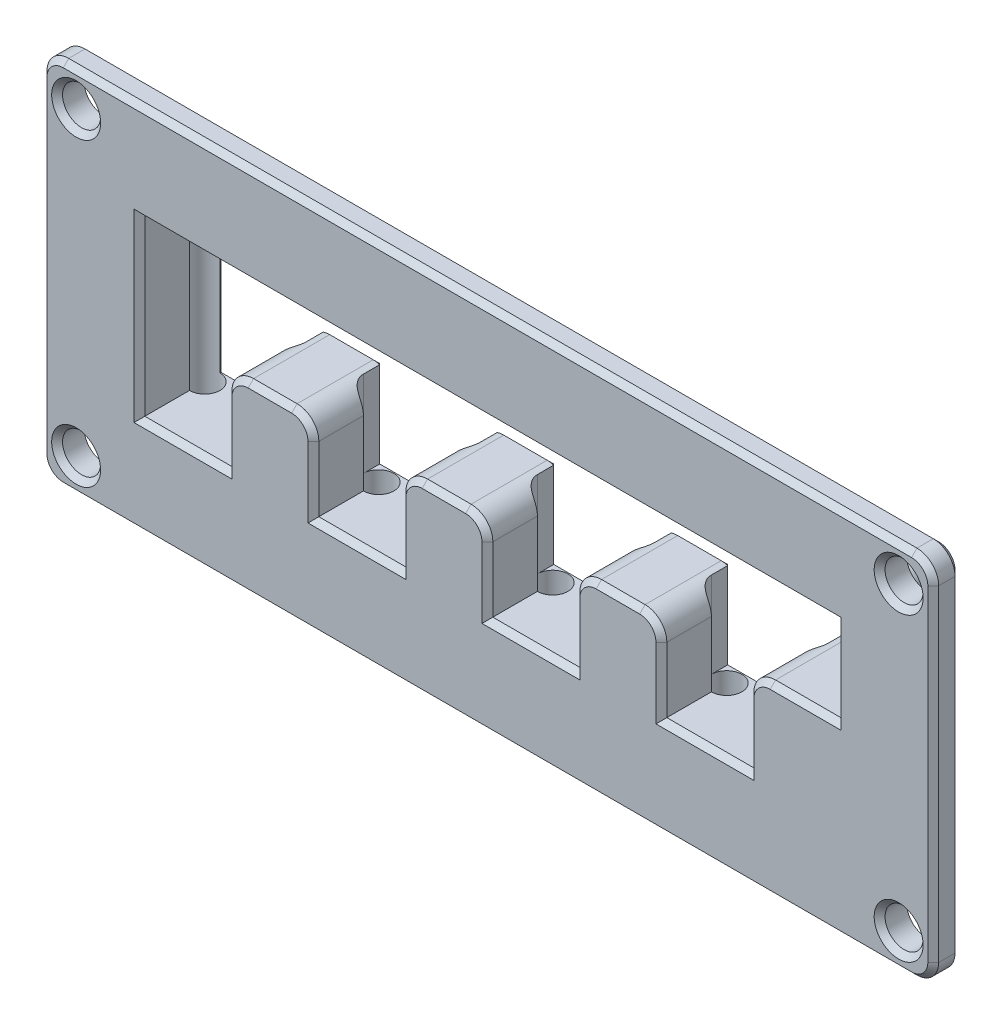
SolidWorks part; units mm, degrees
ref_plane "Front Plane" through (0, 0, 0) normal (0, 0, 1) x (1, 0, 0)
ref_plane "Top Plane" through (0, 0, 0) normal (0, 1, 0) x (1, 0, 0)
ref_plane "Right Plane" through (0, 0, 0) normal (1, 0, 0) x (0, 0, -1)
sketch "Sketch1" plane through (0, 0, 0) normal (0, 0, 1) x (1, 0, 0)
  line L0 (-35, 3) -> (35, 3)
  line L1 (-35, 3) -> (-35, -19)
  line L2 (35, 3) -> (35, -19)
  line L3 (-35, -19) -> (35, -19)
  line L4 (0, 0) -> (0, 3) construction
  line L5 (-32, -8) -> (-35, -8) construction
  line L6 (-32, 0) -> (-32, -16) construction
  line L7 (32, 0) -> (-32, 0) construction
  line L8 (-32, -16) -> (-24, -16) construction
  line L9 (-24, -16) -> (-24, -8) construction
  line L10 (-24, -8) -> (-16, -8) construction
  line L11 (-16, -8) -> (-16, -16) construction
  line L12 (-16, -16) -> (-8, -16) construction
  line L13 (-8, -16) -> (-8, -8) construction
  line L14 (-8, -8) -> (0, -8) construction
  line L15 (0, -8) -> (0, -16) construction
  line L16 (0, -16) -> (8, -16) construction
  line L17 (8, -16) -> (8, -8) construction
  line L18 (8, -8) -> (16, -8) construction
  line L19 (16, -8) -> (16, -16) construction
  line L20 (16, -16) -> (24, -16) construction
  line L21 (24, -16) -> (24, -8) construction
  line L22 (24, -8) -> (32, -8) construction
  line L23 (32, -8) -> (32, 0) construction
  line L24 (-32, 0) -> (-32, -16)
  line L25 (32, 0) -> (-32, 0)
  line L26 (-32, -16) -> (-24, -16)
  line L27 (-24, -16) -> (-24, -8)
  line L28 (-24, -8) -> (-16, -8)
  line L29 (-16, -8) -> (-16, -16)
  line L30 (-16, -16) -> (-8, -16)
  line L31 (-8, -16) -> (-8, -8)
  line L32 (-8, -8) -> (0, -8)
  line L33 (0, -8) -> (0, -16)
  line L34 (0, -16) -> (8, -16)
  line L35 (8, -16) -> (8, -8)
  line L36 (8, -8) -> (16, -8)
  line L37 (16, -8) -> (16, -16)
  line L38 (16, -16) -> (24, -16)
  line L39 (24, -16) -> (24, -8)
  line L40 (24, -8) -> (32, -8)
  line L41 (32, -8) -> (32, 0)
  dimension "D1" = 3
extrude "Boss-Extrude1" add sketch "Sketch1" against normal blind 8
sketch "Sketch2" plane through (0, 0, 0) normal (0, 0, 1) x (1, 0, 0)
  line L0 (0, 3) -> (0, 9) construction
  line L1 (-41, 9) -> (41, 9)
  line L2 (-41, 9) -> (-41, -25)
  line L3 (-41, -25) -> (41, -25)
  line L4 (41, 9) -> (41, -25)
  line L5 (-35, 3) -> (35, 3)
  line L6 (-35, 3) -> (-35, -19)
  line L7 (-35, -19) -> (35, -19)
  line L8 (35, 3) -> (35, -19)
  line L9 (-35, -8) -> (-41, -8) construction
  dimension "D1" = 6
extrude "Boss-Extrude2" add sketch "Sketch2" against normal blind 2.5
sketch "Sketch6" plane through (0, 0, -2.5) normal (0, 0, -1) x (-1, 0, 0)
  line L0 (35, -19) -> (37.818, -21.818) construction
  line L2 (-41, 9) -> (-37.818, 5.818) construction
  line L3 (-37.818, 5.818) -> (-35, 3) construction
  line L4 (37.818, -21.818) -> (-37.818, -21.818) construction
  line L5 (37.818, -21.818) -> (37.818, 5.818) construction
  line L6 (37.818, 5.818) -> (-37.818, 5.818) construction
  line L7 (-37.818, -21.818) -> (-37.818, 5.818) construction
  line L8 (38.7669, -18.2768) -> (35.2256, -19.2256) construction
  line L9 (35.2256, -19.2256) -> (34.2768, -22.7669) construction
  line L10 (34.2768, -22.7669) -> (36.8691, -25.3593) construction
  line L11 (36.8691, -25.3593) -> (40.4104, -24.4104) construction
  line L12 (40.4104, -24.4104) -> (41.3593, -20.8691) construction
  line L13 (41.3593, -20.8691) -> (38.7669, -18.2768) construction
  line L14 (37.818, -21.818) -> (41, -25) construction
  circle A0 centre (37.818, -21.818) radius 1.75
  circle A1 centre (37.818, -21.818) radius 3.175 construction
  circle A2 centre (37.818, -21.818) radius 3.6662 construction
  circle A3 centre (-37.818, 5.818) radius 1.75
  circle A4 centre (37.818, 5.818) radius 1.75
  circle A5 centre (-37.818, -21.818) radius 1.75
  dimension "D1" = 3.5
  dimension "D2" = 6.35
  dimension "D3" = 4.5
extrude "Cut-Extrude3" cut sketch "Sketch6" against normal up to next
fillet "Fillet1" radius 2 15 edges at (24, -8, -4) (16, -8, -4) (8, -8, -4) (0, -8, -4) (-8, -8, -4) (-16, -8, -4) (-24, -8, -4) (-41, -25, -1.25) (-41, 9, -1.25) (-35, -19, -5.25) (-35, 3, -5.25) (35, -19, -5.25) (35, 3, -5.25) (41, -25, -1.25) (41, 9, -1.25)
sketch "Sketch3" plane through (0, 0, 0) normal (0, 1, 0) x (1, 0, 0)
  circle A0 centre (-32, 6) radius 1.2 construction
  arc A1 (-32, 4.8) -> (-32, 7.2) centre (-32, 6) ccw construction
  circle A2 centre (-32, 6) radius 1.4
  dimension "D1" = 0.2
extrude "Cut-Extrude1" cut sketch "Sketch3" against normal through all both and the other way through all
pattern_linear "LPattern1" count 9 spacing 8 along (1, 0, 0) of "Cut-Extrude1"
sketch "Sketch4" plane through (0, 0, 0) normal (1, 0, 0) x (0, 0, -1)
  line L0 (4.875, -21.8042) -> (5.625, -23.1033) construction
  line L1 (8, -19) -> (2.5, -19) construction
  line L2 (8, -17) -> (8, -20)
  line L3 (7, -20) -> (8, -20) construction
  line L4 (6.5, -20.866) -> (4.875, -21.8042)
  line L5 (4.5, -22.4537) -> (4.5, -19) construction
  line L6 (5.625, -23.1033) -> (6.5, -22.5981)
  line L7 (2.5, -23) -> (2.5, 7) construction
  line L12 (2.5, -17) -> (8, -17)
  line L13 (2.5, 1) -> (2.5, -17)
  line L14 (2.5, -17) -> (8, -17)
  line L15 (8, -17) -> (8, 1)
  line L16 (8, 1) -> (2.5, 1)
  line L17 (8, 1) -> (2.5, 1)
  arc A0 (6, -19) -> (6.5, -20.866) centre (6, -20) cw
  arc A1 (8, -20) -> (6.5, -22.5981) centre (5, -20) cw
  arc A2 (4.875, -21.8042) -> (5.625, -23.1033) centre (5.25, -22.4537) ccw
  dimension "D4" = 1
  dimension "D1" = 1.5
  dimension "D2" = 1
  dimension "D3" = 2
  dimension "D5" = 30
  dimension "D6" = 0
extrude "Boss-Extrude3" [suppressed] add sketch "Sketch4" along normal up to surface and the other way up to surface
sketch "Sketch5" [suppressed] plane through (0, -19, 0) normal (0, -1, 0) x (1, 0, 0)
  line L0 (-35, -3) -> (35, -3) construction
  line L1 (-35, -3) -> (-30.6, -3)
  line L2 (-35, -3) -> (-35, -10)
  line L3 (-35, -10) -> (-30.6, -10)
  line L4 (-30.6, -3) -> (-30.6, -10)
  line L5 (-17.4, -3) -> (-6.6, -3)
  line L6 (-17.4, -3) -> (-17.4, -10)
  line L7 (-17.4, -10) -> (-6.6, -10)
  line L8 (-6.6, -3) -> (-6.6, -10)
  line L9 (35, -10) -> (-35, -10) construction
  line L10 (6.6, -3) -> (17.4, -3)
  line L11 (6.6, -3) -> (6.6, -10)
  line L12 (6.6, -10) -> (17.4, -10)
  line L13 (17.4, -3) -> (17.4, -10)
  line L14 (30.6, -3) -> (35, -3)
  line L15 (30.6, -3) -> (30.6, -10)
  line L16 (30.6, -10) -> (35, -10)
  line L17 (35, -3) -> (35, -10)
  circle A0 centre (-32, -5) radius 1.4 construction
  circle A1 centre (-16, -5) radius 1.4 construction
  circle A2 centre (-8, -5) radius 1.4 construction
  circle A3 centre (8, -5) radius 1.4 construction
  circle A4 centre (16, -5) radius 1.4 construction
  circle A5 centre (32, -5) radius 1.4 construction
  circle A6 centre (-24, -5) radius 2
  circle A7 centre (0, -5) radius 2
  circle A8 centre (24, -5) radius 2
  circle A9 centre (-24, -5) radius 1.4 construction
  circle A10 centre (0, -5) radius 1.4 construction
  circle A11 centre (24, -5) radius 1.4 construction
  dimension "D1" = 4
extrude "Cut-Extrude2" [suppressed] cut sketch "Sketch5" along normal through all
mirror "Mirror1" [suppressed]
ref_plane "Plane1" through (0, 0, -6) normal (0, 0, 1) x (1, 0, 0)
sketch "Sketch7" plane through (0, 0, -6) normal (0, 0, 1) x (1, 0, 0)
  line L0 (-24, -10) -> (-24, -16) construction
  line L1 (-24, -8.0921) -> (-22.6, -8.0921)
  line L2 (-24, -8.0921) -> (-24, -16)
  line L3 (-24, -16) -> (-22.6, -16)
  line L4 (-22.6, -8.0921) -> (-22.6, -16)
  line L5 (-20, -8) -> (-20, -19) construction
  line L6 (-24, -16) -> (-25.4, -16) construction
  line L9 (-33, -19) -> (33, -19) construction
  line L10 (-22, -8) -> (-18, -8) construction
extrude "Cut-Extrude5" cut sketch "Sketch7" against normal up to surface (2 mm away)
ref_plane "Plane2" through (-20, 0, 0) normal (1, 0, 0) x (0, 0, -1)
mirror "Mirror2" about plane through (-20, 0, 0) normal (1, 0, 0) of "Cut-Extrude5"
pattern_linear "LPattern3" count 4 spacing 16 along (1, 0, 0) of "Cut-Extrude5"
pattern_linear "LPattern4" count 3 spacing 16 along (1, 0, 0) of "Mirror2"
chamfer "Chamfer1" distance 0.5 angle 45 78 edges at (-40.4142, 8.4142, -2.5) (-40.4142, 8.4142, 0) (0, 9, 0) (40.4142, 8.4142, -2.5) (40.4142, 8.4142, 0) (41, -8, 0) (40.4142, -24.4142, -2.5) (40.4142, -24.4142, 0) (0, -25, 0) (-40.4142, -24.4142, -2.5) (-40.4142, -24.4142, 0) (-41, -8, 0) (32, -4, -8) (32, -4, 0) (0, 0, 0) (0, 0, -8) (-32, -8, 0) (-32, -8, -8) (-28, -16, 0) (-24, -13, 0) (-23.4142, -8.5858, 0) (-20, -8, 0) (-20, -8, -8) (-16.5858, -8.5858, 0) (-16, -13, 0) (-12, -16, 0) (-8, -13, 0) (-7.4142, -8.5858, 0) (-4, -8, 0) (-4, -8, -8) (-0.5858, -8.5858, 0) (0, -13, 0) (4, -16, 0) (8, -13, 0) (8.5858, -8.5858, 0) (12, -8, 0) (12, -8, -8) (15.4142, -8.5858, 0) (16, -13, 0) (20, -16, 0) (24, -13, 0) (24.5858, -8.5858, 0) (29, -8, -8) (29, -8, 0) (-36.068, -21.818, 0) (39.568, 5.818, 0) (-36.068, 5.818, 0) (39.568, -21.818, 0) (34.4142, -18.4142, -8) (35, -8, -8) (34.4142, 2.4142, -8) (0, 3, -8) (-34.4142, 2.4142, -8) (-35, -8, -8) (-34.4142, -18.4142, -8) (0, -19, -8) (20, -16, -8) (14.3035, -8.0232, -8) (9.6965, -8.0232, -8) (4, -16, -8) (-1.6965, -8.0232, -8) (-6.3035, -8.0232, -8) (-12, -16, -8) (-17.6965, -8.0232, -8) (-22.3035, -8.0232, -8) (-27.3, -16, -8) (25.6965, -8.0232, -8) (-41, -8, -2.5) (0, -25, -2.5) (0, 9, -2.5) (41, -8, -2.5) (-22.6, -12.0461, -8) (9.4, -12.0461, -8) (-1.4, -12.0461, -8) (-6.6, -12.0461, -8) (-17.4, -12.0461, -8) (25.4, -12.0461, -8) (14.6, -12.0461, -8)
